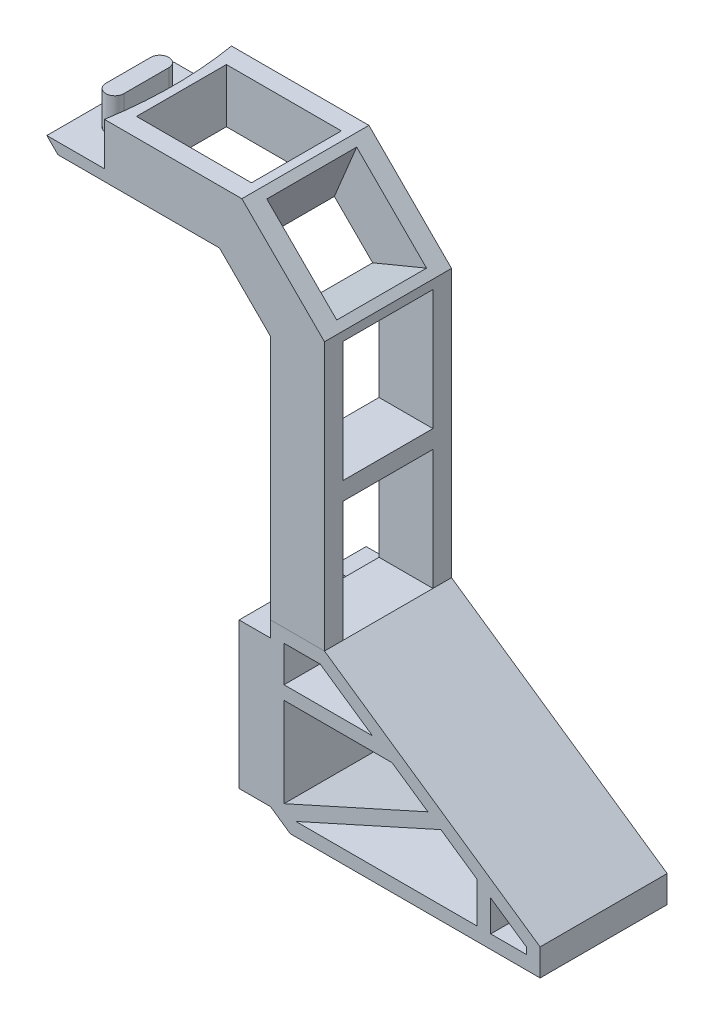
SolidWorks part; units mm, degrees
ref_plane "Front Plane" through (0, 0, 0) normal (0, 0, 1) x (1, 0, 0)
ref_plane "Top Plane" through (0, 0, 0) normal (0, 1, 0) x (1, 0, 0)
ref_plane "Right Plane" through (0, 0, 0) normal (1, 0, 0) x (0, 0, -1)
sketch "Sketch1" plane through (0, 0, 0) normal (0, 0, 1) x (1, 0, 0)
  line L9 (0.7071, 0) -> (0.7071, 18)
  line L11 (30.7071, -1.5118) -> (2.9045, -1.5118)
  line L15 (6.7071, 18) -> (30.7071, 1.4882)
  line L16 (30.7071, 1.4882) -> (30.7071, -1.5118)
  line L17 (0.7071, 0) -> (2.9045, -1.5118)
  line L20 (0.7071, 18) -> (6.7071, 18)
  line L21 (0.7071, 18) -> (-2.7929, 18) construction
  line L22 (0.7071, 2) -> (0.7071, 18) construction
  dimension "D2" = 3
  dimension "D3" = 6
  dimension "D4" = 30
extrude "Boss-Extrude1" add sketch "Sketch1" along normal blind 14.14
sketch "Sketch2" plane through (0, 0, 14.14) normal (0, 0, 1) x (1, 0, 0)
  line L12 (2.2071, 12.5) -> (12.055, 12.5)
  line L15 (2.2071, 11) -> (14.2352, 11)
  line L16 (25.2071, 3.4514) -> (25.2071, -0.0118)
  line L17 (23.7071, 4.4834) -> (23.7071, -0.0118)
  line L24 (2.2071, 1.0395) -> (18.219, 8.2592)
  line L30 (3.5248, -0.0118) -> (19.6638, 7.2652)
  line L87 (6.2409, 16.5) -> (2.2071, 16.5)
  line L88 (29.2071, 0.6995) -> (6.2409, 16.5)
  line L89 (29.2071, -0.0118) -> (29.2071, 0.6995)
  line L90 (3.3707, -0.0118) -> (29.2071, -0.0118)
  line L91 (2.2071, 0.7887) -> (3.3707, -0.0118)
  line L92 (2.2071, 16.5) -> (2.2071, 0.7887)
  line L93 (6.2409, 16.5) -> (2.2071, 16.5)
  line L94 (29.2071, 0.6995) -> (6.2409, 16.5)
  line L95 (29.2071, -0.0118) -> (29.2071, 0.6995)
  line L96 (3.3707, -0.0118) -> (29.2071, -0.0118)
  line L97 (2.2071, 0.7887) -> (3.3707, -0.0118)
  line L98 (2.2071, 16.5) -> (2.2071, 0.7887)
  point P3 (14.962, 10.5)
  point P6 (16.8041, 9.2327)
  point P10 (14.0731, 11.1116)
  point P12 (25.2071, -0.0118)
  point P14 (23.7071, -0.0118)
  point P16 (16.3065, 9.575)
  point P17 (18.2244, 8.2555)
  point P18 (19.5553, 7.3399)
  point P19 (22.9454, 5.0075)
  point P21 (25.6157, 3.1703)
  point P23 (26.2434, 2.7741)
  point P24 (3.9319, -0.0118)
  point P25 (2.2071, 1.0086)
  point P26 (3.5248, -0.0118)
  point P27 (2.2071, 13.0896)
  point P28 (2.2071, 10.8665)
  point P29 (2.2071, 10.6129)
  point P30 (12.624, 12.1129)
  dimension "D5" = 4
  dimension "D2" = 1.5
  dimension "D3" = 1.5
  dimension "D4" = 1.5
  dimension "D6" = 4
  dimension "D7" = 24.27
  dimension "D8" = 20.1823
  dimension "D1" = 1.5
extrude "Cut-Extrude1" cut sketch "Sketch2" against normal up to next
sketch "Sketch3" plane through (0, 0, 14.14) normal (0, 0, 1) x (1, 0, 0)
  line L9 (6.7071, 47.8076) -> (-2.4853, 57)
  line L19 (0.7071, 18) -> (6.7071, 18)
  line L20 (6.7071, 18) -> (6.7071, 47.8076)
  line L21 (-2.4853, 57) -> (-17.1927, 57)
  line L25 (0.7071, 45.3223) -> (0.7071, 18)
  line L26 (-17.1927, 57) -> (-17.1927, 52.2381)
  line L27 (0.7071, 45.3223) -> (-4.9706, 51)
  line L29 (-4.9706, 51) -> (-17.1927, 51) construction
  line L30 (0.7071, 24) -> (0.7071, 45.3223) construction
  line L31 (0.7071, 24) -> (0.7071, 24) construction
  line L33 (-4.9706, 51) -> (-22.9547, 51)
  line L34 (-22.9547, 51) -> (-24.1927, 52.2381)
  line L35 (-24.1927, 52.2381) -> (-17.1927, 52.2381)
  line L37 (-17.1927, 52.2381) -> (-17.1927, 58.2381) construction
  dimension "D1" = 33
  dimension "D2" = 135
  dimension "D3" = 6
  dimension "D4" = 13
  dimension "D6" = 1.2381
  dimension "D7" = 7
  dimension "D9" = 135
extrude "Boss-Extrude2" add sketch "Sketch3" against normal up to surface (14.14 mm away) separate body up to face at (5.6775, 14.5, 0)
sketch "Sketch4" plane through (0, 57, 0) normal (0, 1, 0) x (1, 0, 0)
  line L1 (-2.4853, -14.14) -> (-17.1927, -14.14) construction
  line L4 (-2.4853, 0) -> (-17.1927, 0) construction
  line L8 (-17.7797, 0) -> (-17.1927, 0)
  line L9 (-17.1927, 0) -> (-17.1927, -14.14)
  line L10 (-17.1927, -14.14) -> (-17.7797, -14.14)
  arc A2 (-17.7797, 0) -> (-17.7797, -14.14) centre (-60.0685, -7.07) cw
  circle A3 centre (-60.0685, -7.07) radius 42.8758 construction
  line M7 (-17.1927, 0) -> (-17.1927, -14.14)
extrude "Boss-Extrude8" add sketch "Sketch4" against normal up to next contours L9 A2 L10 | L8 A2 M7
sketch "Sketch9" plane through (0, 52.2381, 0) normal (0, 1, 0) x (1, 0, 0)
  line L0 (-21.1927, -4.57) -> (-21.1927, -9.57) construction
  line L1 (-20.1927, -4.57) -> (-20.1927, -9.57)
  line L2 (-22.1927, -4.57) -> (-22.1927, -9.57)
  line L3 (-24.1927, 0) -> (-24.1927, -14.14) construction
  arc A0 (-20.1927, -4.57) -> (-22.1927, -4.57) centre (-21.1927, -4.57) ccw
  arc A1 (-22.1927, -9.57) -> (-20.1927, -9.57) centre (-21.1927, -9.57) ccw
  point P4 (-21.1927, -7.07)
  point P17 (-24.1927, -7.07)
  dimension "D1" = 3
  dimension "D2" = 2
  dimension "D3" = 5
extrude "Boss-Extrude5" add sketch "Sketch9" along normal blind 3.75
sketch "Sketch10" plane through (0.7071, 0, 0) normal (-1, 0, 0) x (0, 0, 1)
  line L0 (0, 0) -> (14.14, 0)
  line L1 (14.14, 0) -> (14.14, 1.75)
  line L2 (14.14, 18) -> (14.14, 0) construction
  line L3 (14.14, 1.75) -> (0, 1.75)
  line L4 (0, 18) -> (0, 0) construction
  line L5 (0, 1.75) -> (0, 0)
  dimension "D1" = 1.75
extrude "Boss-Extrude6" add sketch "Sketch10" along normal blind 3.5
sketch "Sketch11" plane through (0, 1.75, 0) normal (0, 1, 0) x (1, 0, 0)
  line L0 (0.7071, -14.14) -> (-2.7929, -14.14)
  line L1 (-2.7929, -14.14) -> (-2.7929, -10.14)
  line L2 (-2.7929, 0) -> (0.7071, 0)
  line L3 (0.7071, 0) -> (0.7071, -1.75)
  line L4 (0.7071, -14.14) -> (0.7071, 0) construction
  line L5 (0.7071, -1.75) -> (-1.0429, -1.75)
  line L6 (-1.0429, -1.75) -> (-1.0429, -4)
  line L7 (-1.0429, -11.89) -> (0.7071, -11.89)
  line L8 (0.7071, -11.89) -> (0.7071, -14.14)
  line L9 (-0.7929, -12.14) -> (0.7071, -12.14) construction
  line L10 (-0.7929, -12.14) -> (-0.7929, -2) construction
  line L11 (-0.7929, -2) -> (0.7071, -2) construction
  line L12 (-2.7929, -10.14) -> (-1.0429, -10.14)
  line L13 (-2.7929, -4) -> (-1.0429, -4)
  line L14 (-1.0429, -10.14) -> (-1.0429, -11.89)
  line L15 (-2.7929, -4) -> (-2.7929, 0)
  dimension "D1" = 0.25
  dimension "D2" = 0.25
  dimension "D3" = 0.25
  dimension "D4" = 4
  dimension "D5" = 4
extrude "Boss-Extrude7" add sketch "Sketch11" along normal offset from surface (14.5 mm away) 0.25
ref_plane "Plane1" through (0, 0, 7.07) normal (0, 0, -1) x (-1, 0, 0)
sketch "Sketch15" plane through (0, 0, 7.07) normal (0, 0, -1) x (-1, 0, 0)
  line L0 (2.4853, 57) -> (17.7797, 57) construction
  line L1 (4.9706, 51) -> (5.9706, 51) construction
  line L2 (22.9547, 51) -> (4.9706, 51) construction
  line L3 (16.2797, 51) -> (16.2797, 57)
  line L4 (17.7797, 52.2381) -> (17.7797, 57) construction
  line L5 (-6.7071, 46.8076) -> (-0.7071, 44.3223)
  line L6 (-6, 48.5147) -> (0, 46.0294)
  line L7 (1.7782, 56.2929) -> (4.2635, 50.2929)
  line L8 (3.4853, 57) -> (5.9706, 51)
  line L9 (-6.7071, 47.8076) -> (2.4853, 57) construction
  line L10 (-0.7071, 18) -> (-0.7071, 45.3223)
  line L11 (-0.7071, 45.3223) -> (4.9706, 51)
  line L12 (4.9706, 51) -> (22.9547, 51)
  line L13 (22.9547, 51) -> (24.1927, 52.2381)
  line L14 (24.1927, 52.2381) -> (17.7797, 52.2381)
  line L15 (17.7797, 52.2381) -> (17.7797, 57)
  line L16 (17.7797, 57) -> (2.4853, 57)
  line L17 (2.4853, 57) -> (-6.7071, 47.8076)
  line L18 (-6.7071, 47.8076) -> (-6.7071, 18)
  line L19 (-6.7071, 18) -> (-0.7071, 18)
  line L20 (-0.7071, 18) -> (-0.7071, 31.4038)
  line L21 (-0.7071, 45.3223) -> (0, 46.0294) construction
  line L26 (16.2797, 57) -> (3.4853, 57)
  line L27 (2.4853, 57) -> (1.7782, 56.2929) construction
  line L28 (-6.7071, 47.8076) -> (-6.7071, 46.8076) construction
  line L29 (-6.7071, 18) -> (-0.7071, 18)
  line L30 (1.7782, 56.2929) -> (-6, 48.5147)
  line L31 (3.4853, 57) -> (2.4853, 57) construction
  line L32 (5.9706, 51) -> (16.2797, 51)
  line L34 (4.2635, 50.2929) -> (4.9706, 51) construction
  line L35 (0, 46.0294) -> (4.2635, 50.2929)
  line L36 (-0.7071, 44.3223) -> (-0.7071, 45.3223) construction
  line L37 (-6.7071, 46.8076) -> (-6.7071, 33.4038)
  line L38 (-6, 48.5147) -> (-6.7071, 47.8076) construction
  line L39 (-6.7071, 33.4038) -> (-0.7071, 33.4038)
  line L40 (-6.7071, 31.4038) -> (-0.7071, 31.4038)
  line L41 (-6.7071, 33.4038) -> (-6.7071, 31.4038) construction
  line L42 (-6.7071, 31.4038) -> (-6.7071, 18)
  line L43 (-0.7071, 31.4038) -> (-0.7071, 33.4038) construction
  line L44 (-0.7071, 33.4038) -> (-0.7071, 44.3223)
  dimension "D2" = 1.5
  dimension "D5" = 1
  dimension "D6" = 1
  dimension "D4" = 1
  dimension "D7" = 1
  dimension "D8" = 1
  dimension "D3" = 1
  dimension "D9" = 2
extrude "Cut-Extrude7" cut sketch "Sketch15" against normal mid plane 10
equation "\"D5@Sketch11\"=\"D4@Sketch11\""
equation "\"D4@Sketch15\"=\"D5@Sketch15\""
equation "\"D8@Sketch15\"=\"D7@Sketch15\""
equation "\"D3@Sketch15\"=\"D7@Sketch15\""
equation "\"D3@Sketch2\"=\"D2@Sketch2\""
equation "\"D4@Sketch2\"=\"D3@Sketch2\""
